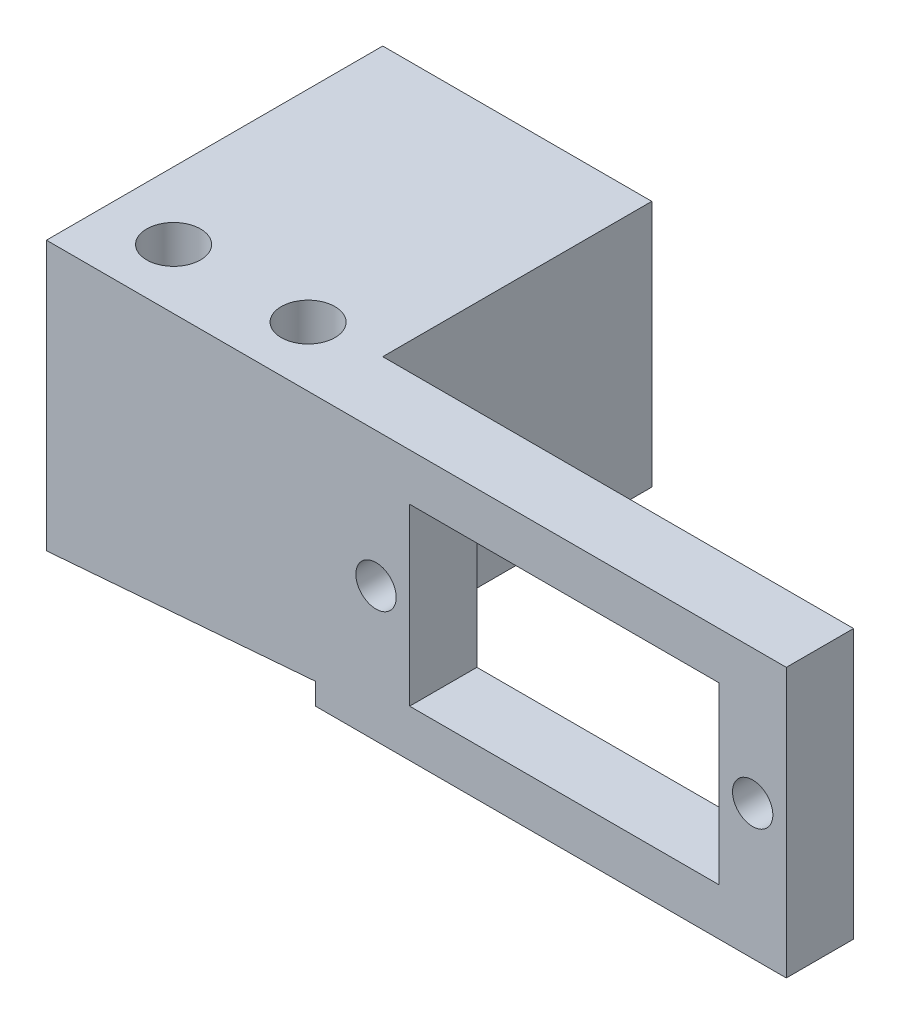
SolidWorks part; units mm, degrees
ref_plane "Plan de face" through (0, 0, 0) normal (0, 0, 1) x (1, 0, 0)
ref_plane "Plan de dessus" through (0, 0, 0) normal (0, 1, 0) x (1, 0, 0)
ref_plane "Plan de droite" through (0, 0, 0) normal (1, 0, 0) x (0, 0, -1)
sketch "Esquisse1" plane through (0, 0, 0) normal (0, 0, 1) x (1, 0, 0)
  line L1 (-28.3333, 8.3333) -> (26.6667, 8.3333)
  line L2 (-28.3333, 8.3333) -> (-28.3333, -11.6667)
  line L3 (-28.3333, -11.6667) -> (26.6667, -11.6667)
  line L4 (26.6667, 8.3333) -> (26.6667, -11.6667)
  dimension "D1" = 20
  dimension "D2" = 55
extrude "Boss.-Extru.1" add sketch "Esquisse1" along normal blind 10
sketch "Esquisse2" plane through (0, 8.3333, 0) normal (0, 1, 0) x (1, 0, 0)
  line L1 (-28.3333, -10) -> (-28.3333, 0) construction
  circle A0 centre (-23.3333, -5.5481) radius 2
  circle A1 centre (-13.3333, -5.5481) radius 2
  dimension "D1" = 4
  dimension "D2" = 4
  dimension "D3" = 5
  dimension "D4" = 15
extrude "Enlèv. mat.-Extru.1" cut sketch "Esquisse2" against normal blind 20
sketch "Esquisse3" plane through (0, 0, 10) normal (0, 0, 1) x (1, 0, 0)
  line L0 (26.6667, -11.6667) -> (26.6667, 8.3333) construction
  line L1 (21.6667, 4.8333) -> (-1.3333, 4.8333)
  line L2 (21.6667, 4.8333) -> (21.6667, -8.1667)
  line L3 (21.6667, -8.1667) -> (-1.3333, -8.1667)
  line L4 (-1.3333, 4.8333) -> (-1.3333, -8.1667)
  line L5 (26.6667, 8.3333) -> (-28.3333, 8.3333) construction
  line L6 (-28.3333, -11.6667) -> (26.6667, -11.6667) construction
  circle A0 centre (24.1667, -1.6667) radius 1.5
  circle A1 centre (-3.8333, -1.6667) radius 1.5
  dimension "D5" = 10
  dimension "D6" = 10
  dimension "D7" = 3
  dimension "D8" = 3
  dimension "D9" = 2.5
  dimension "D10" = 2.5
  dimension "D1" = 23
  dimension "D2" = 13
  dimension "D3" = 5
  dimension "D4" = 3.5
extrude "Enlèv. mat.-Extru.2" cut sketch "Esquisse3" against normal blind 20
sketch "Esquisse5" plane through (0, 0, 0) normal (0, 0, -1) x (-1, 0, 0)
  line L0 (28.3333, -11.6667) -> (28.3333, 8.3333)
  line L1 (28.3333, 8.3333) -> (8.3333, 8.3333)
  line L2 (-26.6667, 8.3333) -> (28.3333, 8.3333) construction
  line L3 (8.3333, 8.3333) -> (8.3333, -10.0667)
  line L4 (8.3333, -10.0667) -> (28.3333, -11.6667)
  line L5 (28.3333, -11.6667) -> (-26.6667, -11.6667) construction
  dimension "D1" = 1.6
  dimension "D2" = 20
extrude "Boss.-Extru.2" add sketch "Esquisse5" along normal blind 15
sketch "Esquisse6" plane through (0, 0, 0) normal (0, 0, -1) x (-1, 0, 0)
  line L0 (8.3333, -10.0667) -> (8.3333, -11.6667)
  line L1 (28.3333, -11.6667) -> (-26.6667, -11.6667) construction
  line L2 (8.3333, -11.6667) -> (28.3333, -11.6667)
  line L3 (28.3333, -11.6667) -> (8.3333, -10.0667)
extrude "Enlèv. mat.-Extru.3" cut sketch "Esquisse6" against normal blind 15
sketch "Esquisse7" plane through (0, 0, 0) normal (0, 0, -1) x (-1, 0, 0)
  line L1 (-26.6667, -11.6667) -> (8.3333, -11.6667)
  line L2 (-26.6667, -11.6667) -> (-26.6667, 8.3333)
  line L3 (-26.6667, 8.3333) -> (8.3333, 8.3333)
  line L4 (8.3333, -11.6667) -> (8.3333, 8.3333)
extrude "Enlèv. mat.-Extru.4" cut sketch "Esquisse7" against normal blind 5
